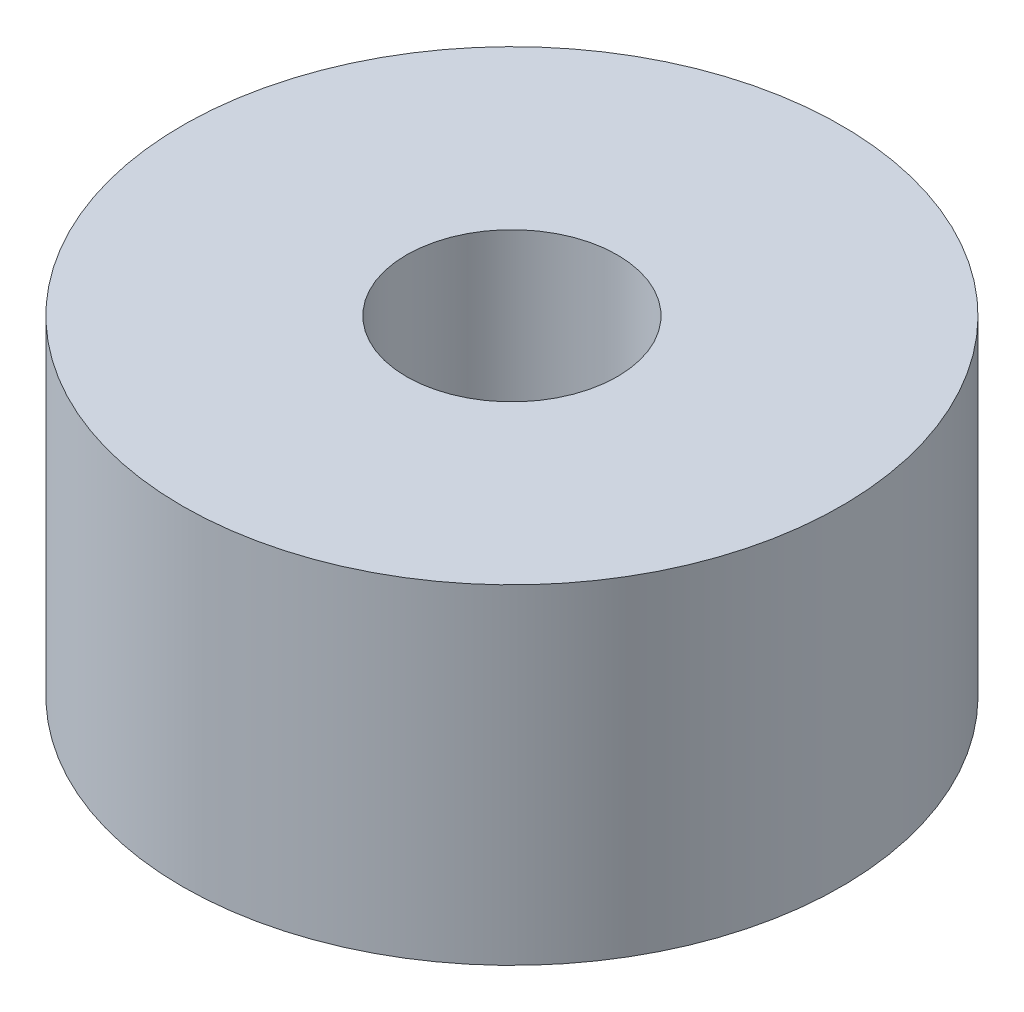
SolidWorks part; units mm, degrees
ref_plane "正面" through (0, 0, 0) normal (0, 0, 1) x (1, 0, 0)
ref_plane "平面" through (0, 0, 0) normal (0, 1, 0) x (1, 0, 0)
ref_plane "右側面" through (0, 0, 0) normal (1, 0, 0) x (0, 0, -1)
sketch "ｽｹｯﾁ1" plane through (0, 0, 0) normal (0, 1, 0) x (1, 0, 0)
  circle A0 centre (0, 0) radius 1.6
  circle A1 centre (0, 0) radius 5
  dimension "D1" = 3.2
  dimension "D2" = 10
extrude "ﾎﾞｽ - 押し出し1" add sketch "ｽｹｯﾁ1" along normal blind 5
